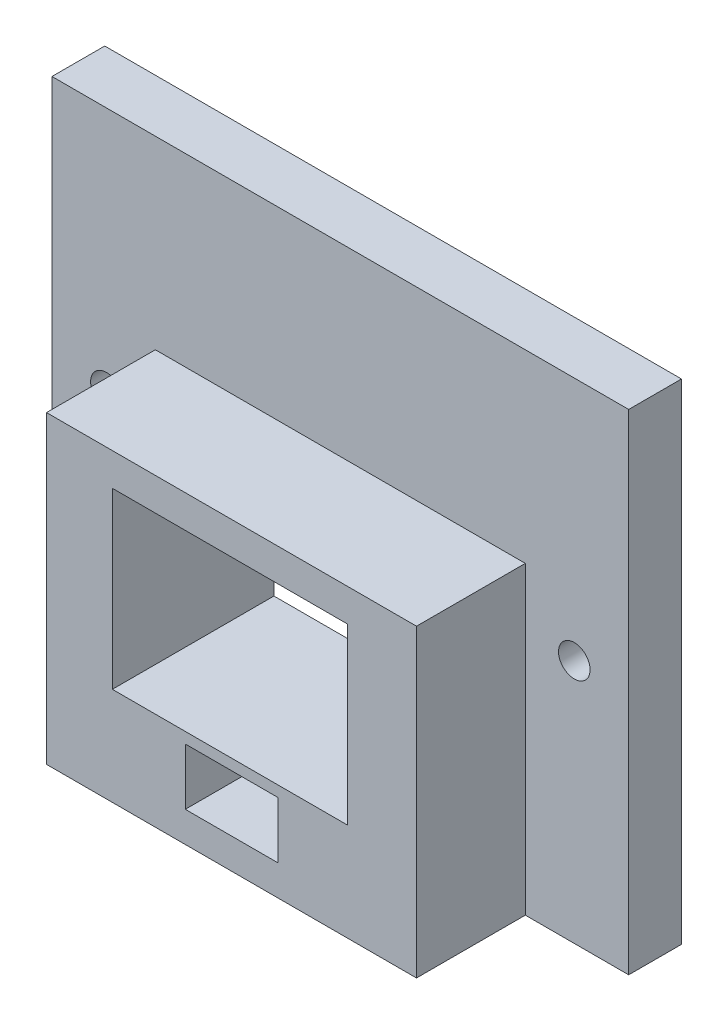
SolidWorks part; units mm, degrees
ref_plane "Alzado" through (0, 0, 0) normal (0, 0, 1) x (1, 0, 0)
ref_plane "Planta" through (0, 0, 0) normal (0, 1, 0) x (1, 0, 0)
ref_plane "Vista lateral" through (0, 0, 0) normal (1, 0, 0) x (0, 0, -1)
sketch "Croquis1" plane through (0, 0, 0) normal (0, 0, 1) x (1, 0, 0)
  line L0 (-26.5, -22.5) -> (0, -22.5) construction
  line L1 (-26.5, 22.5) -> (26.5, 22.5)
  line L2 (-26.5, 22.5) -> (-26.5, -22.5)
  line L3 (-26.5, -22.5) -> (26.5, -22.5)
  line L4 (26.5, 22.5) -> (26.5, -22.5)
  line L5 (-10.95, -13.5) -> (10.6641, -13.5)
  line L7 (-10.95, -13.5) -> (-10.95, 2.5)
  line L8 (-10.95, 2.5) -> (10.6641, 2.5)
  line L10 (-4.25, -17.1) -> (-4.25, -22.5) construction
  line L11 (-4.25, -19.7) -> (4.25, -19.7)
  line L12 (-4.25, -19.7) -> (-4.25, -14.5)
  line L13 (-4.25, -14.5) -> (4.25, -14.5)
  line L14 (4.25, -19.7) -> (4.25, -14.5)
  line L15 (10.6641, -13.5) -> (10.6641, 2.5)
  point P5 (0, -22.5)
  point P6 (-26.5, 0)
  dimension "D1" = 53
  dimension "D2" = 45
  dimension "D3" = 5.4
  dimension "D4" = 1
  dimension "D5" = 16
  dimension "D8" = 8.5
extrude "Saliente-Extruir1" add sketch "Croquis1" along normal blind 14.85
sketch "Croquis2" plane through (0, 0, 14.85) normal (0, 0, 1) x (1, 0, 0)
  line L0 (-26.5, -22.5) -> (26.5, -22.5) construction
  line L1 (26.5, 22.5) -> (17, 22.5)
  line L2 (26.5, 22.5) -> (26.5, -22.5)
  line L3 (26.5, -22.5) -> (17, -22.5)
  line L4 (17, 22.5) -> (17, -22.5)
  line L6 (-26.5, 22.5) -> (-17, 22.5)
  line L7 (-26.5, 22.5) -> (-26.5, -22.5)
  line L8 (-26.5, -22.5) -> (-17, -22.5)
  line L9 (-17, 22.5) -> (-17, -22.5)
  dimension "D1" = 9.5
  dimension "D2" = 9.5
extrude "Cortar-Extruir1" cut sketch "Croquis2" against normal blind 10
sketch "Croquis3" plane through (0, 0, 14.85) normal (0, 0, 1) x (1, 0, 0)
  line L0 (17, 22.5) -> (17, -22.5) construction
  line L1 (-17, 22.5) -> (17, 22.5)
  line L2 (-17, 22.5) -> (-17, 5.5)
  line L3 (-17, 5.5) -> (17, 5.5)
  line L4 (17, 22.5) -> (17, 5.5)
  dimension "D1" = 17
extrude "Cortar-Extruir2" cut sketch "Croquis3" against normal blind 10
sketch "Croquis4" plane through (0, 0, 4.85) normal (0, 0, 1) x (1, 0, 0)
  line L0 (-26.5, 22.5) -> (-26.5, 0) construction
  line L1 (-26.5, 22.5) -> (-26.5, -22.5) construction
  line L2 (-26.5, 0) -> (-21.5, 0) construction
  line L3 (0, 22.5) -> (0, -22.5) construction
  line L4 (26.5, 22.5) -> (-26.5, 22.5) construction
  line L5 (-17, -22.5) -> (17, -22.5) construction
  circle A0 centre (-21.5, 0) radius 1.45
  circle A1 centre (21.5, 0) radius 1.45
  dimension "D2" = 2.9
  dimension "D1" = 5
extrude "Cortar-Extruir3" cut sketch "Croquis4" against normal blind 10
sketch "Croquis5" plane through (0, 0, 4.85) normal (0, 0, 1) x (1, 0, 0)
  line L0 (26.5, -22.5) -> (26.5, 22.5) construction
  line L1 (-26.5, 22.5) -> (26.5, 22.5)
  line L4 (26.5, 22.5) -> (26.5, 5.5)
